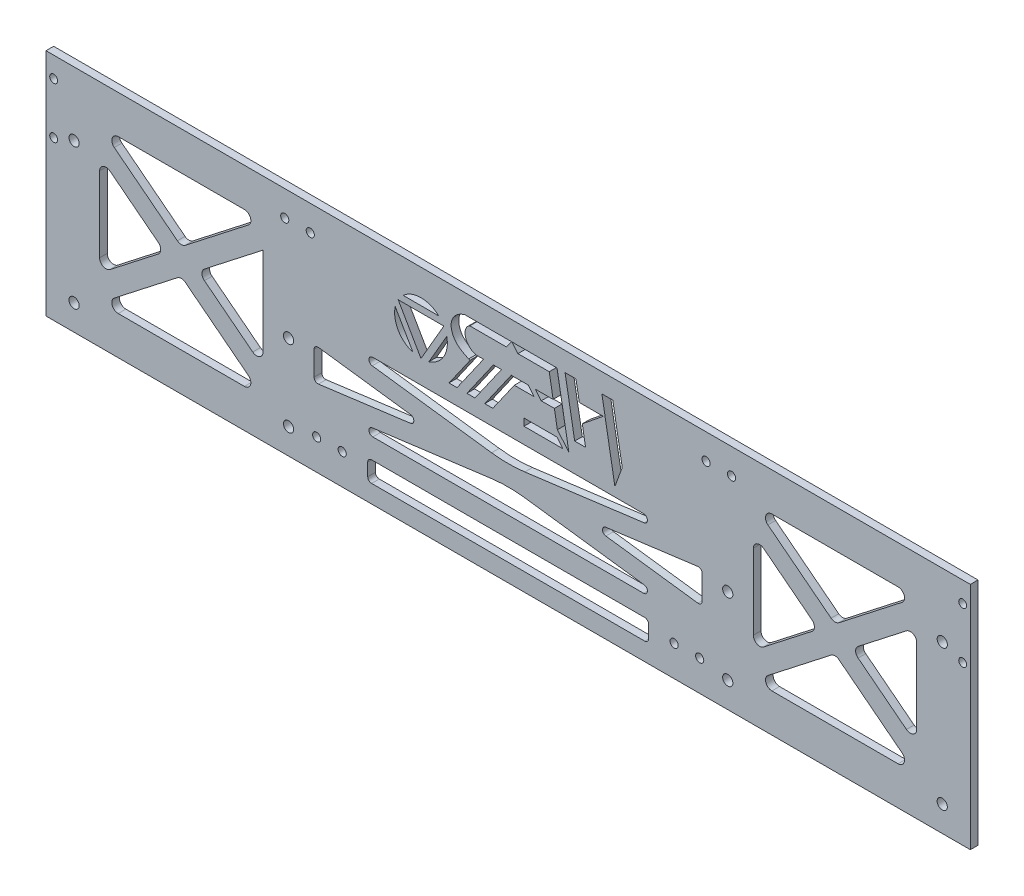
SolidWorks part; units mm, degrees
material "Thornel Mat VMA"
ref_plane "前视基准面" through (0, 0, 0) normal (0, 0, 1) x (1, 0, 0)
ref_plane "上视基准面" through (0, 0, 0) normal (0, 1, 0) x (1, 0, 0)
ref_plane "右视基准面" through (0, 0, 0) normal (1, 0, 0) x (0, 0, -1)
sketch "草图1" plane through (0, 0, 0) normal (0, 0, 1) x (1, 0, 0)
  line L0 (0, -66.0885) -> (0, 68.7386) construction
  line L1 (-181, 45) -> (181, 45)
  line L2 (-181, 45) -> (-181, -45)
  line L3 (-181, -45) -> (181, -45)
  line L4 (181, 45) -> (181, -45)
  line L5 (-181, 45) -> (181, -45) construction
  line L6 (-181, -45) -> (181, 45) construction
  line L7 (-178.6807, 0) -> (188.7068, 0) construction
  circle A0 centre (-170, 20) radius 2
  circle A1 centre (-170, -35) radius 2
  circle A2 centre (170, 20) radius 2
  circle A3 centre (170, -35) radius 2
  circle A4 centre (-86, -5) radius 2
  circle A5 centre (-86, -35) radius 2
  circle A6 centre (86, -5) radius 2
  circle A7 centre (86, -35) radius 2
  point P0 (0, 0)
  dimension "D3" = 4
  dimension "D5" = 55
  dimension "D6" = 10
  dimension "D7" = 4
  dimension "D8" = 30
  dimension "D9" = 10
  dimension "D10" = 172
  dimension "D1" = 362
  dimension "D2" = 90
  dimension "D4" = 340
extrude "凸台-拉伸1" add sketch "草图1" along normal blind 3
sketch "草图2" plane through (0, 0, 3) normal (0, 0, 1) x (1, 0, 0)
  line L0 (0, 67.964) -> (0, -62.1746) construction
  line L1 (-181, -45) -> (181, -45) construction
  line L2 (181, 45) -> (-181, 45) construction
  circle A0 centre (-75, -33) radius 1.6
  circle A1 centre (-65, -33) radius 1.6
  circle A2 centre (65, -33) radius 1.6
  circle A3 centre (75, -33) radius 1.6
  circle A4 centre (-87.5, 35) radius 1.6
  circle A5 centre (-77.5, 35) radius 1.6
  circle A6 centre (77.5, 35) radius 1.6
  circle A7 centre (87.5, 35) radius 1.6
  dimension "D1" = 3.2
  dimension "D2" = 10
  dimension "D3" = 10
  dimension "D4" = 130
  dimension "D5" = 12
  dimension "D6" = 10
  dimension "D7" = 10
  dimension "D8" = 155
  dimension "D9" = 3.2
  dimension "D10" = 10
extrude "切除-拉伸1" cut sketch "草图2" against normal through all
sketch "草图4" plane through (0, 0, 3) normal (0, 0, 1) x (1, 0, 0)
  line L98 (0, 0) -> (0, 45) construction
  line L100 (-55, -30) -> (55, -30)
  line L101 (-55, -30) -> (-55, -38)
  line L151 (-55, -38) -> (55, -38)
  line L152 (181, 45) -> (-181, 45) construction
  line L153 (-181, 23) -> (181, 23) construction
  line L154 (-181, 45) -> (-181, -45) construction
  line L155 (181, -45) -> (181, 45) construction
  line L156 (-31.0382, 14.4981) -> (-24.0629, 26.5798)
  line L157 (-25.2014, 29.5077) -> (-34.1432, 14.0202)
  line L158 (-34.1432, 14.0202) -> (-43.0849, 29.5077)
  line L159 (-43.0849, 29.5077) -> (-25.2014, 29.5077)
  line L160 (-16.1694, 11.2202) -> (-5.7977, 26.0325)
  line L161 (-5.7977, 26.0325) -> (-2.6359, 26.0325)
  line L162 (-2.6359, 26.0325) -> (-13.0076, 11.2202)
  line L163 (-13.0076, 11.2202) -> (-16.1694, 11.2202)
  line L164 (-14.7655, 23.2325) -> (-15.4655, 23.2325)
  line L165 (-16.9316, 37.4702) -> (1.2684, 37.4702)
  line L166 (1.2684, 37.4702) -> (-0.6922, 34.6702)
  line L167 (-0.6922, 34.6702) -> (-15.0377, 34.6702)
  line L168 (-12.2727, 26.0325) -> (-9.6432, 26.0325)
  line L169 (-9.6432, 26.0325) -> (-20.0148, 11.2202)
  line L170 (-20.0148, 11.2202) -> (-23.1767, 11.2202)
  line L171 (-23.1767, 11.2202) -> (-14.7655, 23.2325)
  line L172 (3.8278, 34.6702) -> (1.4784, 37.4702)
  line L173 (1.4784, 37.4702) -> (19.1381, 37.4702)
  line L174 (19.1381, 37.4702) -> (23.7667, 11.2202)
  line L175 (23.7667, 11.2202) -> (19.2672, 16.5825)
  line L176 (19.2672, 16.5825) -> (18.0946, 23.2325)
  line L177 (18.0946, 23.2325) -> (12.9504, 23.2325)
  line L178 (12.9504, 23.2325) -> (10.6009, 26.0325)
  line L179 (10.6009, 26.0325) -> (17.6009, 26.0325)
  line L180 (17.6009, 26.0325) -> (16.0778, 34.6702)
  line L181 (16.0778, 34.6702) -> (3.8278, 34.6702)
  line L182 (10.209, 23.2325) -> (2.4108, 23.2325)
  line L183 (2.4108, 23.2325) -> (-6.0004, 11.2202)
  line L184 (-6.0004, 11.2202) -> (-9.1622, 11.2202)
  line L185 (-9.1622, 11.2202) -> (1.2095, 26.0325)
  line L186 (1.2095, 26.0325) -> (7.8595, 26.0325)
  line L187 (7.8595, 26.0325) -> (10.209, 23.2325)
  line L188 (-44.2234, 26.5798) -> (-37.2481, 14.4981)
  line L189 (41.7976, 8.5768) -> (36.7029, 37.4702)
  line L190 (36.7029, 37.4702) -> (40.9677, 37.4702)
  line L191 (40.9677, 37.4702) -> (44.6706, 16.4702)
  line L192 (44.6706, 16.4702) -> (41.7976, 8.5768)
  line L193 (-27.1678, 31.9577) -> (-41.1185, 31.9577)
  line L194 (21.4822, 11.2202) -> (6.1827, 11.2202)
  line L195 (6.1827, 11.2202) -> (6.1827, 14.0202)
  line L196 (6.1827, 14.0202) -> (19.1327, 14.0202)
  line L197 (19.1327, 14.0202) -> (21.4822, 11.2202)
  line L198 (29.0215, 23.4702) -> (30.3175, 16.1202)
  line L199 (30.3175, 16.1202) -> (26.0527, 16.1202)
  line L200 (26.0527, 16.1202) -> (22.2881, 37.4702)
  line L201 (22.2881, 37.4702) -> (26.5529, 37.4702)
  line L202 (26.5529, 37.4702) -> (27.8489, 30.1202)
  line L203 (27.8489, 30.1202) -> (37.2335, 30.1202)
  line L204 (37.2335, 30.1202) -> (29.0215, 23.4702)
  line L205 (0, 0) -> (0, -74.1458) construction
  line L210 (-181, -45) -> (181, -45) construction
  line L211 (-76, 5) -> (76, 5)
  line L212 (-76, 5) -> (-76, -22)
  line L213 (-76, -22) -> (76, -22)
  line L214 (76, 5) -> (76, -22)
  line L215 (-181, -45) -> (181, -45) construction
  line L216 (160, 30) -> (96, 30)
  line L217 (160, 30) -> (160, -30)
  line L218 (160, -30) -> (96, -30)
  line L219 (96, 30) -> (96, -30)
  line L220 (160, 30) -> (96, -30) construction
  line L221 (160, -30) -> (96, 30) construction
  line L222 (-96, 30) -> (-160, 30)
  line L223 (-96, 30) -> (-96, -30)
  line L224 (-96, -30) -> (-160, -30)
  line L225 (-160, 30) -> (-160, -30)
  line L226 (-96, 30) -> (-160, -30) construction
  line L227 (-96, -30) -> (-160, 30) construction
  line L228 (181, 45) -> (-181, 45) construction
  line L229 (55, -30) -> (55, -38)
  line L230 (-55, -30) -> (55, -38) construction
  line L231 (-55, -38) -> (55, -30) construction
  arc A9 (-24.0629, 26.5798) -> (-31.0382, 14.4981) centre (-34.1432, 24.3452) cw
  arc A10 (-37.2481, 14.4981) -> (-44.2234, 26.5798) centre (-34.1432, 24.3452) cw
  arc A11 (-41.1185, 31.9577) -> (-27.1678, 31.9577) centre (-34.1432, 24.3452) cw
  circle A12 centre (-86, -5) radius 2 construction
  circle A13 centre (86, -5) radius 2 construction
  circle A14 centre (170, 20) radius 2 construction
  circle A15 centre (-65, -33) radius 1.6 construction
  spline S0 degree 3 poles (-15.4655, 23.2325) (-15.5413, 23.2696) (-21.0497, 25.3869) (-22.7695, 30.9584) (-21.899, 33.698) (-20.1307, 36.232) (-18.2747, 37.0945) (-16.9316, 37.4702) knots 0 0 0 0 0.322817 0.607041 0.715415 0.780271 1 1 1 1
  spline S1 degree 3 poles (-15.0377, 34.6702) (-16.4933, 33.8959) (-17.8912, 29.7452) (-14.538, 26.3064) (-12.2727, 26.0325) knots 0 0 0 0 0.403414 1 1 1 1
  point P10 (0, 22.5)
  point P11 (0, 23)
  point P58 (0, -34)
  point P75 (-128, 0)
  point P80 (128, 0)
  dimension "D1" = 22
  dimension "D2" = 10
  dimension "D3" = 23
  dimension "D4" = 27
  dimension "D5" = 10
  dimension "D6" = 10
  dimension "D7" = 15
  dimension "D8" = 15
  dimension "D9" = 8
  dimension "D10" = 8
  dimension "D11" = 10
extrude "切除-拉伸2" cut sketch "草图4" against normal through all
sketch "草图5" plane through (0, 0, 0) normal (0, 0, -1) x (-1, 0, 0)
  line L0 (-160, 30) -> (-128, 5.0706)
  line L1 (-96, 30) -> (-96, -30) construction
  line L2 (-96, -19.8589) -> (-96, -30)
  line L3 (-96, -30) -> (-128, -5.0706)
  line L4 (-160, -30) -> (-160, 30) construction
  line L5 (-160, 19.8589) -> (-160, 30)
  line L6 (-96, 30) -> (-128, 5.0706)
  line L7 (-160, -19.8589) -> (-160, -30)
  line L8 (-160, -30) -> (-128, -5.0706)
  line L9 (-96, 19.8589) -> (-96, 30)
  line L10 (96, 30) -> (128, 5.0706)
  line L11 (160, 30) -> (160, -30) construction
  line L12 (160, -19.8589) -> (160, -30)
  line L13 (160, -30) -> (128, -5.0706)
  line L14 (96, -30) -> (96, 30) construction
  line L15 (96, 19.8589) -> (96, 30)
  line L16 (160, 30) -> (128, 5.0706)
  line L17 (96, -19.8589) -> (96, -30)
  line L18 (96, -30) -> (128, -5.0706)
  line L19 (160, 19.8589) -> (160, 30)
  line L20 (-121.4913, 0) -> (-96, 19.8589)
  line L21 (-121.4913, 0) -> (-96, -19.8589)
  line L22 (-134.5087, 0) -> (-160, -19.8589)
  line L23 (-134.5087, 0) -> (-160, 19.8589)
  line L24 (134.5087, 0) -> (160, 19.8589)
  line L25 (134.5087, 0) -> (160, -19.8589)
  line L26 (121.4913, 0) -> (96, -19.8589)
  line L27 (121.4913, 0) -> (96, 19.8589)
  line L28 (76, 5) -> (0, -4.97)
  line L29 (-76, -22) -> (-76, 5) construction
  line L30 (-76, -14.94) -> (-76, -22)
  line L31 (-76, -22) -> (0, -12.03)
  line L32 (76, 5) -> (76, -22) construction
  line L33 (76, -2.06) -> (76, 5)
  line L34 (-76, 5) -> (0, -4.97)
  line L35 (76, -14.94) -> (76, -22)
  line L36 (76, -22) -> (0, -12.03)
  line L37 (-76, -2.06) -> (-76, 5)
  line L38 (-26.9086, -8.5) -> (-76, -2.06)
  line L39 (-26.9086, -8.5) -> (-76, -14.94)
  line L40 (26.9086, -8.5) -> (76, -14.94)
  line L41 (26.9086, -8.5) -> (76, -2.06)
  dimension "D1" = 8
  dimension "D2" = 7
extrude "凸台-拉伸2" add sketch "草图5" against normal up to surface (3 mm away) up to face at (1.0877, 20.1617, 3)
fillet "圆角2" radius 2.5 23 edges at (-121.4913, 0, 1.5) (-96, -19.8589, 1.5) (-96, -30, 1.5) (-128, -5.0706, 1.5) (-160, -30, 1.5) (-160, -19.8589, 1.5) (-160, 19.8589, 1.5) (-134.5087, 0, 1.5) (-128, 5.0706, 1.5) (-160, 30, 1.5) (-96, 30, 1.5) (160, 19.8589, 1.5) (134.5087, 0, 1.5) (160, -19.8589, 1.5) (160, -30, 1.5) (128, -5.0706, 1.5) (96, -30, 1.5) (96, -19.8589, 1.5) (96, 19.8589, 1.5) (121.4913, 0, 1.5) (128, 5.0706, 1.5) (96, 30, 1.5) (160, 30, 1.5)
fillet "圆角3" radius 1.5 14 edges at (55, -38, 1.5) (55, -30, 1.5) (-55, -38, 1.5) (-55, -30, 1.5) (-26.9086, -8.5, 1.5) (26.9086, -8.5, 1.5) (76, -22, 1.5) (-76, -22, 1.5) (76, 5, 1.5) (-76, 5, 1.5) (76, -14.94, 1.5) (76, -2.06, 1.5) (-76, -14.94, 1.5) (-76, -2.06, 1.5)
fillet "圆角4" radius 50 2 edges at (0, -4.97, 1.5) (0, -12.03, 1.5)
sketch "草图6" plane through (0, 0, 3) normal (0, 0, 1) x (1, 0, 0)
  line L0 (0, 71.6292) -> (0, -77.2307) construction
  line L1 (181, -45) -> (181, 45) construction
  line L2 (181, 45) -> (-181, 45) construction
  circle A0 centre (-178, 37) radius 1.55
  circle A1 centre (-178, 17) radius 1.55
  circle A2 centre (178, 37) radius 1.55
  circle A4 centre (178, 17) radius 1.55
  dimension "D1" = 3.1
  dimension "D2" = 20
  dimension "D3" = 3
  dimension "D4" = 8
extrude "切除-拉伸3" cut sketch "草图6" against normal through all
